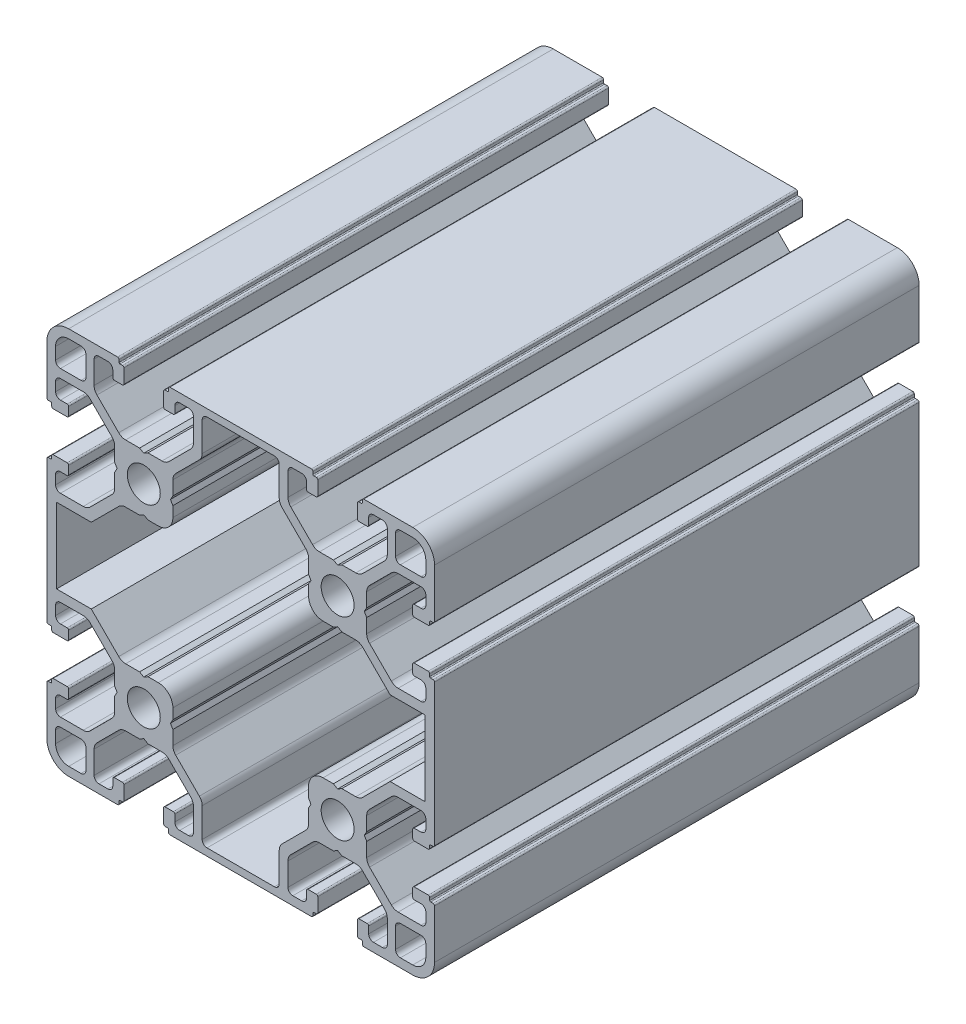
SolidWorks part; units mm, degrees
ref_plane "前视基准面" through (0, 0, 0) normal (0, 0, 1) x (1, 0, 0)
ref_plane "上视基准面" through (0, 0, 0) normal (0, 1, 0) x (1, 0, 0)
ref_plane "右视基准面" through (0, 0, 0) normal (1, 0, 0) x (0, 0, -1)
sketch "草图1" plane through (0, 0, 0) normal (0, 0, 1) x (1, 0, 0)
  line L0 (-19.9196, 14.4542) -> (-17.7856, 14.4542)
  line L1 (-20.7856, 14.9542) -> (-19.9196, 14.4542)
  line L2 (-14.7856, 17.4542) -> (-14.7856, 19.5882)
  line L3 (-21.6516, 14.4542) -> (-20.7856, 14.9542)
  line L4 (-14.7856, 19.5882) -> (-15.2856, 20.4542)
  line L5 (-24.543, 14.4542) -> (-21.6516, 14.4542)
  line L6 (-15.2856, 20.4542) -> (-14.7856, 21.3202)
  line L7 (-14.7856, 21.3202) -> (-14.7856, 24.2116)
  line L8 (-31.6214, 8.2042) -> (-25.9572, 13.8684)
  line L9 (-38.7856, 8.2042) -> (-31.6214, 8.2042)
  line L10 (-14.1998, 25.6258) -> (-9.3214, 30.5042)
  line L11 (-38.7856, -7.2958) -> (-38.7856, 8.2042)
  line L12 (-31.6214, -7.2958) -> (-38.7856, -7.2958)
  line L13 (-8.7356, 31.9184) -> (-8.7356, 37.9542)
  line L14 (-25.9572, -12.96) -> (-31.6214, -7.2958)
  line L15 (-7.7356, 38.9542) -> (6.1644, 38.9542)
  line L16 (-21.6516, -13.5458) -> (-24.543, -13.5458)
  line L17 (-20.7856, -14.0458) -> (-21.6516, -13.5458)
  line L18 (7.1644, 37.9542) -> (7.1644, 31.9184)
  line L19 (-19.9196, -13.5458) -> (-20.7856, -14.0458)
  line L20 (-17.7856, -13.5458) -> (-19.9196, -13.5458)
  line L21 (7.7502, 30.5042) -> (12.6286, 25.6258)
  line L22 (-14.7856, -18.6798) -> (-14.7856, -16.5458)
  line L23 (13.2144, 24.2116) -> (13.2144, 21.3202)
  line L24 (-15.2856, -19.5458) -> (-14.7856, -18.6798)
  line L25 (13.2144, 21.3202) -> (13.7144, 20.4542)
  line L26 (-14.7856, -20.4118) -> (-15.2856, -19.5458)
  line L27 (13.7144, 20.4542) -> (13.2144, 19.5882)
  line L28 (-14.7856, -23.3032) -> (-14.7856, -20.4118)
  line L29 (13.2144, 19.5882) -> (13.2144, 17.4542)
  line L30 (-9.3214, -29.5958) -> (-14.1998, -24.7174)
  line L31 (16.2144, 14.4542) -> (18.3484, 14.4542)
  line L32 (18.3484, 14.4542) -> (19.2144, 14.9542)
  line L33 (-8.7356, -37.0458) -> (-8.7356, -31.01)
  line L34 (19.2144, 14.9542) -> (20.0804, 14.4542)
  line L35 (20.0804, 14.4542) -> (22.9717, 14.4542)
  line L36 (6.1644, -38.0458) -> (-7.7356, -38.0458)
  line L37 (24.386, 13.8684) -> (30.0502, 8.2042)
  line L38 (7.1644, -31.01) -> (7.1644, -37.0458)
  line L39 (30.0502, 8.2042) -> (37.2144, 8.2042)
  line L40 (37.2144, 8.2042) -> (37.2144, -7.2958)
  line L41 (12.6286, -24.7174) -> (7.7502, -29.5958)
  line L42 (37.2144, -7.2958) -> (30.0502, -7.2958)
  line L43 (30.0502, -7.2958) -> (24.386, -12.96)
  line L44 (13.2144, -20.4118) -> (13.2144, -23.3032)
  line L45 (13.7144, -19.5458) -> (13.2144, -20.4118)
  line L46 (22.9717, -13.5458) -> (20.0804, -13.5458)
  line L47 (13.2144, -18.6798) -> (13.7144, -19.5458)
  line L48 (20.0804, -13.5458) -> (19.2144, -14.0458)
  line L49 (13.2144, -16.5458) -> (13.2144, -18.6798)
  line L50 (19.2144, -14.0458) -> (18.3484, -13.5458)
  line L51 (18.3484, -13.5458) -> (16.2144, -13.5458)
  line L52 (-40.7856, -14.1458) -> (-40.7856, 15.0542)
  line L53 (-39.9856, 15.3542) -> (-40.4856, 15.3542)
  line L54 (-39.9856, -14.4458) -> (-40.4856, -14.4458)
  line L55 (-39.7856, 16.0542) -> (-39.7856, 15.5542)
  line L56 (-39.7856, -15.1458) -> (-39.7856, -14.6458)
  line L57 (-36.5856, 16.3542) -> (-39.4856, 16.3542)
  line L58 (-36.5856, -15.4458) -> (-39.4856, -15.4458)
  line L59 (-36.2856, 14.3542) -> (-36.2856, 16.0542)
  line L60 (-36.2856, -13.4458) -> (-36.2856, -15.1458)
  line L61 (-37.9856, 14.0542) -> (-36.5856, 14.0542)
  line L62 (-37.9856, -13.1458) -> (-36.5856, -13.1458)
  line L63 (-38.9856, 11.2042) -> (-38.9856, 13.0542)
  line L64 (-38.9856, -10.2958) -> (-38.9856, -12.1458)
  line L65 (-33.2783, 10.2042) -> (-37.9856, 10.2042)
  line L66 (-33.2783, -9.2958) -> (-37.9856, -9.2958)
  line L67 (-27.3714, 15.2826) -> (-31.864, 10.79)
  line L68 (-27.3714, -14.3742) -> (-31.864, -9.8816)
  line L69 (-26.7856, 19.5882) -> (-26.7856, 16.6968)
  line L70 (-26.2856, 20.4542) -> (-26.7856, 19.5882)
  line L71 (-26.7856, -18.6798) -> (-26.7856, -15.7884)
  line L72 (-26.2856, 20.4542) -> (-26.7856, 21.3202)
  line L73 (-26.2856, -19.5458) -> (-26.7856, -18.6798)
  line L74 (-26.7856, 24.2116) -> (-26.7856, 21.3202)
  line L75 (-26.2856, -19.5458) -> (-26.7856, -20.4118)
  line L76 (-26.7856, -23.3032) -> (-26.7856, -20.4118)
  line L77 (-31.864, 30.1184) -> (-27.3714, 25.6258)
  line L78 (-31.864, -29.21) -> (-27.3714, -24.7174)
  line L79 (-37.9856, 30.7042) -> (-33.2783, 30.7042)
  line L80 (-37.9856, -29.7958) -> (-33.2783, -29.7958)
  line L81 (-38.9856, 27.8542) -> (-38.9856, 29.7042)
  line L82 (-38.9856, -26.9458) -> (-38.9856, -28.7958)
  line L83 (-36.5856, 26.8542) -> (-37.9856, 26.8542)
  line L84 (-36.5856, -25.9458) -> (-37.9856, -25.9458)
  line L85 (-36.2856, 24.8542) -> (-36.2856, 26.5542)
  line L86 (-36.2856, -23.9458) -> (-36.2856, -25.6458)
  line L87 (-39.4856, 24.5542) -> (-36.5856, 24.5542)
  line L88 (-39.4856, -23.6458) -> (-36.5856, -23.6458)
  line L89 (-39.7856, 25.3542) -> (-39.7856, 24.8542)
  line L90 (-39.7856, -24.4458) -> (-39.7856, -23.9458)
  line L91 (-40.4856, 25.5542) -> (-39.9856, 25.5542)
  line L92 (-40.4856, -24.6458) -> (-39.9856, -24.6458)
  line L93 (-40.7856, 35.9542) -> (-40.7856, 25.8542)
  line L94 (-40.7856, -35.0458) -> (-40.7856, -24.9458)
  line L95 (-26.1856, 40.4542) -> (-36.2856, 40.4542)
  line L96 (-26.1856, -39.5458) -> (-36.2856, -39.5458)
  line L97 (-25.8856, 39.6542) -> (-25.8856, 40.1542)
  line L98 (-25.8856, -38.7458) -> (-25.8856, -39.2458)
  line L99 (-25.1856, 39.4542) -> (-25.6856, 39.4542)
  line L100 (-25.1856, -38.5458) -> (-25.6856, -38.5458)
  line L101 (-24.8856, 36.2542) -> (-24.8856, 39.1542)
  line L102 (-24.8856, -35.3458) -> (-24.8856, -38.2458)
  line L103 (-26.8856, 35.9542) -> (-25.1856, 35.9542)
  line L104 (-26.8856, -35.0458) -> (-25.1856, -35.0458)
  line L105 (-27.1856, 37.6542) -> (-27.1856, 36.2542)
  line L106 (-27.1856, -36.7458) -> (-27.1856, -35.3458)
  line L107 (-30.0356, 38.6542) -> (-28.1856, 38.6542)
  line L108 (-30.0356, -37.7458) -> (-28.1856, -37.7458)
  line L109 (-31.0356, 32.9468) -> (-31.0356, 37.6542)
  line L110 (-31.0356, -32.0384) -> (-31.0356, -36.7458)
  line L111 (-25.9572, 27.04) -> (-30.4498, 31.5326)
  line L112 (-25.9572, -26.1316) -> (-30.4498, -30.6242)
  line L113 (-21.6516, 26.4542) -> (-24.543, 26.4542)
  line L114 (-20.7856, 25.9542) -> (-21.6516, 26.4542)
  line L115 (-21.6516, -25.5458) -> (-24.543, -25.5458)
  line L116 (-20.7856, 25.9542) -> (-19.9196, 26.4542)
  line L117 (-20.7856, -25.0458) -> (-21.6516, -25.5458)
  line L118 (-17.0283, 26.4542) -> (-19.9196, 26.4542)
  line L119 (-20.7856, -25.0458) -> (-19.9196, -25.5458)
  line L120 (-17.0283, -25.5458) -> (-19.9196, -25.5458)
  line L121 (-11.1214, 31.5326) -> (-15.614, 27.04)
  line L122 (-11.1214, -30.6242) -> (-15.614, -26.1316)
  line L123 (-10.5356, 37.6542) -> (-10.5356, 32.9468)
  line L124 (-10.5356, -36.7458) -> (-10.5356, -32.0384)
  line L125 (-13.3856, 38.6542) -> (-11.5356, 38.6542)
  line L126 (-13.3856, -37.7458) -> (-11.5356, -37.7458)
  line L127 (-14.3856, 36.2542) -> (-14.3856, 37.6542)
  line L128 (-14.3856, -35.3458) -> (-14.3856, -36.7458)
  line L129 (-16.3856, 35.9542) -> (-14.6856, 35.9542)
  line L130 (-16.3856, -35.0458) -> (-14.6856, -35.0458)
  line L131 (-16.6856, 39.1542) -> (-16.6856, 36.2542)
  line L132 (-16.6856, -38.2458) -> (-16.6856, -35.3458)
  line L133 (-15.8856, 39.4542) -> (-16.3856, 39.4542)
  line L134 (-15.8856, -38.5458) -> (-16.3856, -38.5458)
  line L135 (-15.6856, 40.1542) -> (-15.6856, 39.6542)
  line L136 (-15.6856, -39.2458) -> (-15.6856, -38.7458)
  line L137 (13.8144, 40.4542) -> (-15.3856, 40.4542)
  line L138 (13.8144, -39.5458) -> (-15.3856, -39.5458)
  line L139 (14.1144, 40.1542) -> (14.1144, 39.6542)
  line L140 (14.1144, -39.2458) -> (14.1144, -38.7458)
  line L141 (14.3144, 39.4542) -> (14.8144, 39.4542)
  line L142 (14.3144, -38.5458) -> (14.8144, -38.5458)
  line L143 (15.1144, 39.1542) -> (15.1144, 36.2542)
  line L144 (15.1144, -38.2458) -> (15.1144, -35.3458)
  line L145 (14.8144, 35.9542) -> (13.1144, 35.9542)
  line L146 (14.8144, -35.0458) -> (13.1144, -35.0458)
  line L147 (12.8144, 36.2542) -> (12.8144, 37.6542)
  line L148 (12.8144, -35.3458) -> (12.8144, -36.7458)
  line L149 (11.8144, 38.6542) -> (9.9644, 38.6542)
  line L150 (11.8144, -37.7458) -> (9.9644, -37.7458)
  line L151 (8.9644, 37.6542) -> (8.9644, 32.9468)
  line L152 (8.9644, -36.7458) -> (8.9644, -32.0384)
  line L153 (9.5502, 31.5326) -> (14.0428, 27.04)
  line L154 (9.5502, -30.6242) -> (14.0428, -26.1316)
  line L155 (15.457, 26.4542) -> (18.3484, 26.4542)
  line L156 (19.2144, 25.9542) -> (18.3484, 26.4542)
  line L157 (15.457, -25.5458) -> (18.3484, -25.5458)
  line L158 (19.2144, 25.9542) -> (20.0804, 26.4542)
  line L159 (19.2144, -25.0458) -> (18.3484, -25.5458)
  line L160 (20.0804, 26.4542) -> (22.9717, 26.4542)
  line L161 (19.2144, -25.0458) -> (20.0804, -25.5458)
  line L162 (20.0804, -25.5458) -> (22.9717, -25.5458)
  line L163 (24.386, 27.04) -> (28.8786, 31.5326)
  line L164 (24.386, -26.1316) -> (28.8786, -30.6242)
  line L165 (29.4644, 32.9468) -> (29.4644, 37.6542)
  line L166 (29.4644, -32.0384) -> (29.4644, -36.7458)
  line L167 (28.4644, 38.6542) -> (26.6144, 38.6542)
  line L168 (28.4644, -37.7458) -> (26.6144, -37.7458)
  line L169 (25.6144, 37.6542) -> (25.6144, 36.2542)
  line L170 (25.6144, -36.7458) -> (25.6144, -35.3458)
  line L171 (25.3144, 35.9542) -> (23.6144, 35.9542)
  line L172 (25.3144, -35.0458) -> (23.6144, -35.0458)
  line L173 (23.3144, 36.2542) -> (23.3144, 39.1542)
  line L174 (23.3144, -35.3458) -> (23.3144, -38.2458)
  line L175 (23.6144, 39.4542) -> (24.1144, 39.4542)
  line L176 (23.6144, -38.5458) -> (24.1144, -38.5458)
  line L177 (24.3144, 39.6542) -> (24.3144, 40.1542)
  line L178 (24.3144, -38.7458) -> (24.3144, -39.2458)
  line L179 (24.6144, 40.4542) -> (34.7144, 40.4542)
  line L180 (24.6144, -39.5458) -> (34.7144, -39.5458)
  line L181 (39.2144, 35.9542) -> (39.2144, 25.8542)
  line L182 (39.2144, -35.0458) -> (39.2144, -24.9458)
  line L183 (38.9144, 25.5542) -> (38.4144, 25.5542)
  line L184 (38.9144, -24.6458) -> (38.4144, -24.6458)
  line L185 (38.2144, 25.3542) -> (38.2144, 24.8542)
  line L186 (38.2144, -24.4458) -> (38.2144, -23.9458)
  line L187 (37.9144, 24.5542) -> (35.0144, 24.5542)
  line L188 (37.9144, -23.6458) -> (35.0144, -23.6458)
  line L189 (34.7144, 24.8542) -> (34.7144, 26.5542)
  line L190 (34.7144, -23.9458) -> (34.7144, -25.6458)
  line L191 (35.0144, 26.8542) -> (36.4144, 26.8542)
  line L192 (35.0144, -25.9458) -> (36.4144, -25.9458)
  line L193 (37.4144, 27.8542) -> (37.4144, 29.7042)
  line L194 (37.4144, -26.9458) -> (37.4144, -28.7958)
  line L195 (36.4144, 30.7042) -> (31.707, 30.7042)
  line L196 (36.4144, -29.7958) -> (31.707, -29.7958)
  line L197 (30.2928, 30.1184) -> (25.8002, 25.6258)
  line L198 (30.2928, -29.21) -> (25.8002, -24.7174)
  line L199 (25.2144, 24.2116) -> (25.2144, 21.3202)
  line L200 (24.7144, 20.4542) -> (25.2144, 21.3202)
  line L201 (25.2144, -23.3032) -> (25.2144, -20.4118)
  line L202 (24.7144, 20.4542) -> (25.2144, 19.5882)
  line L203 (24.7144, -19.5458) -> (25.2144, -20.4118)
  line L204 (25.2144, 19.5882) -> (25.2144, 16.6968)
  line L205 (24.7144, -19.5458) -> (25.2144, -18.6798)
  line L206 (25.2144, -18.6798) -> (25.2144, -15.7884)
  line L207 (25.8002, 15.2826) -> (30.2928, 10.79)
  line L208 (25.8002, -14.3742) -> (30.2928, -9.8816)
  line L209 (31.707, 10.2042) -> (36.4144, 10.2042)
  line L210 (31.707, -9.2958) -> (36.4144, -9.2958)
  line L211 (37.4144, 11.2042) -> (37.4144, 13.0542)
  line L212 (37.4144, -10.2958) -> (37.4144, -12.1458)
  line L213 (36.4144, 14.0542) -> (35.0144, 14.0542)
  line L214 (36.4144, -13.1458) -> (35.0144, -13.1458)
  line L215 (34.7144, 14.3542) -> (34.7144, 16.0542)
  line L216 (34.7144, -13.4458) -> (34.7144, -15.1458)
  line L217 (35.0144, 16.3542) -> (37.9144, 16.3542)
  line L218 (35.0144, -15.4458) -> (37.9144, -15.4458)
  line L219 (38.2144, 16.0542) -> (38.2144, 15.5542)
  line L220 (38.2144, -15.1458) -> (38.2144, -14.6458)
  line L221 (38.4144, 15.3542) -> (38.9144, 15.3542)
  line L222 (38.4144, -14.4458) -> (38.9144, -14.4458)
  line L223 (39.2144, -14.1458) -> (39.2144, 15.0542)
  line L224 (-33.7356, 38.6542) -> (-36.2856, 38.6542)
  line L225 (-38.9856, 33.5042) -> (-38.9856, 35.9542)
  line L226 (-32.7356, 33.5042) -> (-32.7356, 37.6542)
  line L227 (-37.9856, 32.5042) -> (-33.7356, 32.5042)
  line L228 (32.1644, 38.6542) -> (34.7144, 38.6542)
  line L229 (37.4144, 35.9542) -> (37.4144, 33.5042)
  line L230 (31.1644, 33.5042) -> (31.1644, 37.6542)
  line L231 (36.4144, 32.5042) -> (32.1644, 32.5042)
  line L232 (-38.9856, -35.0458) -> (-38.9856, -32.5958)
  line L233 (-37.9856, -31.5958) -> (-33.7356, -31.5958)
  line L234 (-33.7356, -37.7458) -> (-36.2856, -37.7458)
  line L235 (-32.7356, -32.5958) -> (-32.7356, -36.7458)
  line L236 (37.4144, -35.0458) -> (37.4144, -32.5958)
  line L237 (32.1644, -37.7458) -> (34.7144, -37.7458)
  line L238 (36.4144, -31.5958) -> (32.1644, -31.5958)
  line L239 (31.1644, -32.5958) -> (31.1644, -36.7458)
  circle A0 centre (19.2144, -19.5458) radius 3.4
  circle A1 centre (-20.7856, -19.5458) radius 3.4
  circle A2 centre (-20.7856, 20.4542) radius 3.4
  circle A3 centre (19.2144, 20.4542) radius 3.4
  arc A4 (-17.7856, 14.4542) -> (-14.7856, 17.4542) centre (-17.7856, 17.4542) ccw
  arc A5 (-24.543, 14.4542) -> (-25.9572, 13.8684) centre (-24.543, 12.4542) ccw
  arc A6 (-14.1998, 25.6258) -> (-14.7856, 24.2116) centre (-12.7856, 24.2116) ccw
  arc A7 (-9.3214, 30.5042) -> (-8.7356, 31.9184) centre (-10.7356, 31.9184) ccw
  arc A8 (-7.7356, 38.9542) -> (-8.7356, 37.9542) centre (-7.7356, 37.9542) ccw
  arc A9 (-25.9572, -12.96) -> (-24.543, -13.5458) centre (-24.543, -11.5458) ccw
  arc A10 (7.1644, 37.9542) -> (6.1644, 38.9542) centre (6.1644, 37.9542) ccw
  arc A11 (7.1644, 31.9184) -> (7.7502, 30.5042) centre (9.1644, 31.9184) ccw
  arc A12 (-14.7856, -16.5458) -> (-17.7856, -13.5458) centre (-17.7856, -16.5458) ccw
  arc A13 (13.2144, 24.2116) -> (12.6286, 25.6258) centre (11.2144, 24.2116) ccw
  arc A14 (-14.7856, -23.3032) -> (-14.1998, -24.7174) centre (-12.7856, -23.3032) ccw
  arc A15 (13.2144, 17.4542) -> (16.2144, 14.4542) centre (16.2144, 17.4542) ccw
  arc A16 (-8.7356, -31.01) -> (-9.3214, -29.5958) centre (-10.7356, -31.01) ccw
  arc A17 (-8.7356, -37.0458) -> (-7.7356, -38.0458) centre (-7.7356, -37.0458) ccw
  arc A18 (24.386, 13.8684) -> (22.9717, 14.4542) centre (22.9717, 12.4542) ccw
  arc A19 (6.1644, -38.0458) -> (7.1644, -37.0458) centre (6.1644, -37.0458) ccw
  arc A20 (7.7502, -29.5958) -> (7.1644, -31.01) centre (9.1644, -31.01) ccw
  arc A21 (12.6286, -24.7174) -> (13.2144, -23.3032) centre (11.2144, -23.3032) ccw
  arc A22 (22.9717, -13.5458) -> (24.386, -12.96) centre (22.9717, -11.5458) ccw
  arc A23 (16.2144, -13.5458) -> (13.2144, -16.5458) centre (16.2144, -16.5458) ccw
  arc A24 (-40.4856, 15.3542) -> (-40.7856, 15.0542) centre (-40.4856, 15.0542) ccw
  arc A25 (-40.7856, -14.1458) -> (-40.4856, -14.4458) centre (-40.4856, -14.1458) ccw
  arc A26 (-39.9856, 15.3542) -> (-39.7856, 15.5542) centre (-39.9856, 15.5542) ccw
  arc A27 (-39.7856, -14.6458) -> (-39.9856, -14.4458) centre (-39.9856, -14.6458) ccw
  arc A28 (-39.4856, 16.3542) -> (-39.7856, 16.0542) centre (-39.4856, 16.0542) ccw
  arc A29 (-39.7856, -15.1458) -> (-39.4856, -15.4458) centre (-39.4856, -15.1458) ccw
  arc A30 (-36.2856, 16.0542) -> (-36.5856, 16.3542) centre (-36.5856, 16.0542) ccw
  arc A31 (-36.5856, -15.4458) -> (-36.2856, -15.1458) centre (-36.5856, -15.1458) ccw
  arc A32 (-36.5856, 14.0542) -> (-36.2856, 14.3542) centre (-36.5856, 14.3542) ccw
  arc A33 (-36.2856, -13.4458) -> (-36.5856, -13.1458) centre (-36.5856, -13.4458) ccw
  arc A34 (-37.9856, 14.0542) -> (-38.9856, 13.0542) centre (-37.9856, 13.0542) ccw
  arc A35 (-38.9856, -12.1458) -> (-37.9856, -13.1458) centre (-37.9856, -12.1458) ccw
  arc A36 (-38.9856, 11.2042) -> (-37.9856, 10.2042) centre (-37.9856, 11.2042) ccw
  arc A37 (-37.9856, -9.2958) -> (-38.9856, -10.2958) centre (-37.9856, -10.2958) ccw
  arc A38 (-33.2783, 10.2042) -> (-31.864, 10.79) centre (-33.2783, 12.2042) ccw
  arc A39 (-31.864, -9.8816) -> (-33.2783, -9.2958) centre (-33.2783, -11.2958) ccw
  arc A40 (-27.3714, 15.2826) -> (-26.7856, 16.6968) centre (-28.7856, 16.6968) ccw
  arc A41 (-26.7856, -15.7884) -> (-27.3714, -14.3742) centre (-28.7856, -15.7884) ccw
  arc A42 (-26.7856, 24.2116) -> (-27.3714, 25.6258) centre (-28.7856, 24.2116) ccw
  arc A43 (-27.3714, -24.7174) -> (-26.7856, -23.3032) centre (-28.7856, -23.3032) ccw
  arc A44 (-31.864, 30.1184) -> (-33.2783, 30.7042) centre (-33.2783, 28.7042) ccw
  arc A45 (-33.2783, -29.7958) -> (-31.864, -29.21) centre (-33.2783, -27.7958) ccw
  arc A46 (-37.9856, 30.7042) -> (-38.9856, 29.7042) centre (-37.9856, 29.7042) ccw
  arc A47 (-38.9856, -28.7958) -> (-37.9856, -29.7958) centre (-37.9856, -28.7958) ccw
  arc A48 (-38.9856, 27.8542) -> (-37.9856, 26.8542) centre (-37.9856, 27.8542) ccw
  arc A49 (-37.9856, -25.9458) -> (-38.9856, -26.9458) centre (-37.9856, -26.9458) ccw
  arc A50 (-36.2856, 26.5542) -> (-36.5856, 26.8542) centre (-36.5856, 26.5542) ccw
  arc A51 (-36.5856, -25.9458) -> (-36.2856, -25.6458) centre (-36.5856, -25.6458) ccw
  arc A52 (-36.5856, 24.5542) -> (-36.2856, 24.8542) centre (-36.5856, 24.8542) ccw
  arc A53 (-36.2856, -23.9458) -> (-36.5856, -23.6458) centre (-36.5856, -23.9458) ccw
  arc A54 (-39.7856, 24.8542) -> (-39.4856, 24.5542) centre (-39.4856, 24.8542) ccw
  arc A55 (-39.4856, -23.6458) -> (-39.7856, -23.9458) centre (-39.4856, -23.9458) ccw
  arc A56 (-39.7856, 25.3542) -> (-39.9856, 25.5542) centre (-39.9856, 25.3542) ccw
  arc A57 (-39.9856, -24.6458) -> (-39.7856, -24.4458) centre (-39.9856, -24.4458) ccw
  arc A58 (-40.7856, 25.8542) -> (-40.4856, 25.5542) centre (-40.4856, 25.8542) ccw
  arc A59 (-40.4856, -24.6458) -> (-40.7856, -24.9458) centre (-40.4856, -24.9458) ccw
  arc A60 (-36.2856, 40.4542) -> (-40.7856, 35.9542) centre (-36.2856, 35.9542) ccw
  arc A61 (-40.7856, -35.0458) -> (-36.2856, -39.5458) centre (-36.2856, -35.0458) ccw
  arc A62 (-25.8856, 40.1542) -> (-26.1856, 40.4542) centre (-26.1856, 40.1542) ccw
  arc A63 (-26.1856, -39.5458) -> (-25.8856, -39.2458) centre (-26.1856, -39.2458) ccw
  arc A64 (-25.8856, 39.6542) -> (-25.6856, 39.4542) centre (-25.6856, 39.6542) ccw
  arc A65 (-25.6856, -38.5458) -> (-25.8856, -38.7458) centre (-25.6856, -38.7458) ccw
  arc A66 (-24.8856, 39.1542) -> (-25.1856, 39.4542) centre (-25.1856, 39.1542) ccw
  arc A67 (-25.1856, -38.5458) -> (-24.8856, -38.2458) centre (-25.1856, -38.2458) ccw
  arc A68 (-25.1856, 35.9542) -> (-24.8856, 36.2542) centre (-25.1856, 36.2542) ccw
  arc A69 (-24.8856, -35.3458) -> (-25.1856, -35.0458) centre (-25.1856, -35.3458) ccw
  arc A70 (-27.1856, 36.2542) -> (-26.8856, 35.9542) centre (-26.8856, 36.2542) ccw
  arc A71 (-26.8856, -35.0458) -> (-27.1856, -35.3458) centre (-26.8856, -35.3458) ccw
  arc A72 (-27.1856, 37.6542) -> (-28.1856, 38.6542) centre (-28.1856, 37.6542) ccw
  arc A73 (-28.1856, -37.7458) -> (-27.1856, -36.7458) centre (-28.1856, -36.7458) ccw
  arc A74 (-30.0356, 38.6542) -> (-31.0356, 37.6542) centre (-30.0356, 37.6542) ccw
  arc A75 (-31.0356, -36.7458) -> (-30.0356, -37.7458) centre (-30.0356, -36.7458) ccw
  arc A76 (-31.0356, 32.9468) -> (-30.4498, 31.5326) centre (-29.0356, 32.9468) ccw
  arc A77 (-30.4498, -30.6242) -> (-31.0356, -32.0384) centre (-29.0356, -32.0384) ccw
  arc A78 (-25.9572, 27.04) -> (-24.543, 26.4542) centre (-24.543, 28.4542) ccw
  arc A79 (-24.543, -25.5458) -> (-25.9572, -26.1316) centre (-24.543, -27.5458) ccw
  arc A80 (-17.0283, 26.4542) -> (-15.614, 27.04) centre (-17.0283, 28.4542) ccw
  arc A81 (-15.614, -26.1316) -> (-17.0283, -25.5458) centre (-17.0283, -27.5458) ccw
  arc A82 (-11.1214, 31.5326) -> (-10.5356, 32.9468) centre (-12.5356, 32.9468) ccw
  arc A83 (-10.5356, -32.0384) -> (-11.1214, -30.6242) centre (-12.5356, -32.0384) ccw
  arc A84 (-10.5356, 37.6542) -> (-11.5356, 38.6542) centre (-11.5356, 37.6542) ccw
  arc A85 (-11.5356, -37.7458) -> (-10.5356, -36.7458) centre (-11.5356, -36.7458) ccw
  arc A86 (-13.3856, 38.6542) -> (-14.3856, 37.6542) centre (-13.3856, 37.6542) ccw
  arc A87 (-14.3856, -36.7458) -> (-13.3856, -37.7458) centre (-13.3856, -36.7458) ccw
  arc A88 (-14.6856, 35.9542) -> (-14.3856, 36.2542) centre (-14.6856, 36.2542) ccw
  arc A89 (-14.3856, -35.3458) -> (-14.6856, -35.0458) centre (-14.6856, -35.3458) ccw
  arc A90 (-16.6856, 36.2542) -> (-16.3856, 35.9542) centre (-16.3856, 36.2542) ccw
  arc A91 (-16.3856, -35.0458) -> (-16.6856, -35.3458) centre (-16.3856, -35.3458) ccw
  arc A92 (-16.3856, 39.4542) -> (-16.6856, 39.1542) centre (-16.3856, 39.1542) ccw
  arc A93 (-16.6856, -38.2458) -> (-16.3856, -38.5458) centre (-16.3856, -38.2458) ccw
  arc A94 (-15.8856, 39.4542) -> (-15.6856, 39.6542) centre (-15.8856, 39.6542) ccw
  arc A95 (-15.6856, -38.7458) -> (-15.8856, -38.5458) centre (-15.8856, -38.7458) ccw
  arc A96 (-15.3856, 40.4542) -> (-15.6856, 40.1542) centre (-15.3856, 40.1542) ccw
  arc A97 (-15.6856, -39.2458) -> (-15.3856, -39.5458) centre (-15.3856, -39.2458) ccw
  arc A98 (14.1144, 40.1542) -> (13.8144, 40.4542) centre (13.8144, 40.1542) ccw
  arc A99 (13.8144, -39.5458) -> (14.1144, -39.2458) centre (13.8144, -39.2458) ccw
  arc A100 (14.1144, 39.6542) -> (14.3144, 39.4542) centre (14.3144, 39.6542) ccw
  arc A101 (14.3144, -38.5458) -> (14.1144, -38.7458) centre (14.3144, -38.7458) ccw
  arc A102 (15.1144, 39.1542) -> (14.8144, 39.4542) centre (14.8144, 39.1542) ccw
  arc A103 (14.8144, -38.5458) -> (15.1144, -38.2458) centre (14.8144, -38.2458) ccw
  arc A104 (14.8144, 35.9542) -> (15.1144, 36.2542) centre (14.8144, 36.2542) ccw
  arc A105 (15.1144, -35.3458) -> (14.8144, -35.0458) centre (14.8144, -35.3458) ccw
  arc A106 (12.8144, 36.2542) -> (13.1144, 35.9542) centre (13.1144, 36.2542) ccw
  arc A107 (13.1144, -35.0458) -> (12.8144, -35.3458) centre (13.1144, -35.3458) ccw
  arc A108 (12.8144, 37.6542) -> (11.8144, 38.6542) centre (11.8144, 37.6542) ccw
  arc A109 (11.8144, -37.7458) -> (12.8144, -36.7458) centre (11.8144, -36.7458) ccw
  arc A110 (9.9644, 38.6542) -> (8.9644, 37.6542) centre (9.9644, 37.6542) ccw
  arc A111 (8.9644, -36.7458) -> (9.9644, -37.7458) centre (9.9644, -36.7458) ccw
  arc A112 (8.9644, 32.9468) -> (9.5502, 31.5326) centre (10.9644, 32.9468) ccw
  arc A113 (9.5502, -30.6242) -> (8.9644, -32.0384) centre (10.9644, -32.0384) ccw
  arc A114 (14.0428, 27.04) -> (15.457, 26.4542) centre (15.457, 28.4542) ccw
  arc A115 (15.457, -25.5458) -> (14.0428, -26.1316) centre (15.457, -27.5458) ccw
  arc A116 (22.9717, 26.4542) -> (24.386, 27.04) centre (22.9717, 28.4542) ccw
  arc A117 (24.386, -26.1316) -> (22.9717, -25.5458) centre (22.9717, -27.5458) ccw
  arc A118 (28.8786, 31.5326) -> (29.4644, 32.9468) centre (27.4644, 32.9468) ccw
  arc A119 (29.4644, -32.0384) -> (28.8786, -30.6242) centre (27.4644, -32.0384) ccw
  arc A120 (29.4644, 37.6542) -> (28.4644, 38.6542) centre (28.4644, 37.6542) ccw
  arc A121 (28.4644, -37.7458) -> (29.4644, -36.7458) centre (28.4644, -36.7458) ccw
  arc A122 (26.6144, 38.6542) -> (25.6144, 37.6542) centre (26.6144, 37.6542) ccw
  arc A123 (25.6144, -36.7458) -> (26.6144, -37.7458) centre (26.6144, -36.7458) ccw
  arc A124 (25.3144, 35.9542) -> (25.6144, 36.2542) centre (25.3144, 36.2542) ccw
  arc A125 (25.6144, -35.3458) -> (25.3144, -35.0458) centre (25.3144, -35.3458) ccw
  arc A126 (23.3144, 36.2542) -> (23.6144, 35.9542) centre (23.6144, 36.2542) ccw
  arc A127 (23.6144, -35.0458) -> (23.3144, -35.3458) centre (23.6144, -35.3458) ccw
  arc A128 (23.6144, 39.4542) -> (23.3144, 39.1542) centre (23.6144, 39.1542) ccw
  arc A129 (23.3144, -38.2458) -> (23.6144, -38.5458) centre (23.6144, -38.2458) ccw
  arc A130 (24.1144, 39.4542) -> (24.3144, 39.6542) centre (24.1144, 39.6542) ccw
  arc A131 (24.3144, -38.7458) -> (24.1144, -38.5458) centre (24.1144, -38.7458) ccw
  arc A132 (24.6144, 40.4542) -> (24.3144, 40.1542) centre (24.6144, 40.1542) ccw
  arc A133 (24.3144, -39.2458) -> (24.6144, -39.5458) centre (24.6144, -39.2458) ccw
  arc A134 (39.2144, 35.9542) -> (34.7144, 40.4542) centre (34.7144, 35.9542) ccw
  arc A135 (34.7144, -39.5458) -> (39.2144, -35.0458) centre (34.7144, -35.0458) ccw
  arc A136 (38.9144, 25.5542) -> (39.2144, 25.8542) centre (38.9144, 25.8542) ccw
  arc A137 (39.2144, -24.9458) -> (38.9144, -24.6458) centre (38.9144, -24.9458) ccw
  arc A138 (38.4144, 25.5542) -> (38.2144, 25.3542) centre (38.4144, 25.3542) ccw
  arc A139 (38.2144, -24.4458) -> (38.4144, -24.6458) centre (38.4144, -24.4458) ccw
  arc A140 (37.9144, 24.5542) -> (38.2144, 24.8542) centre (37.9144, 24.8542) ccw
  arc A141 (38.2144, -23.9458) -> (37.9144, -23.6458) centre (37.9144, -23.9458) ccw
  arc A142 (34.7144, 24.8542) -> (35.0144, 24.5542) centre (35.0144, 24.8542) ccw
  arc A143 (35.0144, -23.6458) -> (34.7144, -23.9458) centre (35.0144, -23.9458) ccw
  arc A144 (35.0144, 26.8542) -> (34.7144, 26.5542) centre (35.0144, 26.5542) ccw
  arc A145 (34.7144, -25.6458) -> (35.0144, -25.9458) centre (35.0144, -25.6458) ccw
  arc A146 (36.4144, 26.8542) -> (37.4144, 27.8542) centre (36.4144, 27.8542) ccw
  arc A147 (37.4144, -26.9458) -> (36.4144, -25.9458) centre (36.4144, -26.9458) ccw
  arc A148 (37.4144, 29.7042) -> (36.4144, 30.7042) centre (36.4144, 29.7042) ccw
  arc A149 (36.4144, -29.7958) -> (37.4144, -28.7958) centre (36.4144, -28.7958) ccw
  arc A150 (31.707, 30.7042) -> (30.2928, 30.1184) centre (31.707, 28.7042) ccw
  arc A151 (30.2928, -29.21) -> (31.707, -29.7958) centre (31.707, -27.7958) ccw
  arc A152 (25.8002, 25.6258) -> (25.2144, 24.2116) centre (27.2144, 24.2116) ccw
  arc A153 (25.2144, -23.3032) -> (25.8002, -24.7174) centre (27.2144, -23.3032) ccw
  arc A154 (25.2144, 16.6968) -> (25.8002, 15.2826) centre (27.2144, 16.6968) ccw
  arc A155 (25.8002, -14.3742) -> (25.2144, -15.7884) centre (27.2144, -15.7884) ccw
  arc A156 (30.2928, 10.79) -> (31.707, 10.2042) centre (31.707, 12.2042) ccw
  arc A157 (31.707, -9.2958) -> (30.2928, -9.8816) centre (31.707, -11.2958) ccw
  arc A158 (36.4144, 10.2042) -> (37.4144, 11.2042) centre (36.4144, 11.2042) ccw
  arc A159 (37.4144, -10.2958) -> (36.4144, -9.2958) centre (36.4144, -10.2958) ccw
  arc A160 (37.4144, 13.0542) -> (36.4144, 14.0542) centre (36.4144, 13.0542) ccw
  arc A161 (36.4144, -13.1458) -> (37.4144, -12.1458) centre (36.4144, -12.1458) ccw
  arc A162 (34.7144, 14.3542) -> (35.0144, 14.0542) centre (35.0144, 14.3542) ccw
  arc A163 (35.0144, -13.1458) -> (34.7144, -13.4458) centre (35.0144, -13.4458) ccw
  arc A164 (35.0144, 16.3542) -> (34.7144, 16.0542) centre (35.0144, 16.0542) ccw
  arc A165 (34.7144, -15.1458) -> (35.0144, -15.4458) centre (35.0144, -15.1458) ccw
  arc A166 (38.2144, 16.0542) -> (37.9144, 16.3542) centre (37.9144, 16.0542) ccw
  arc A167 (37.9144, -15.4458) -> (38.2144, -15.1458) centre (37.9144, -15.1458) ccw
  arc A168 (38.2144, 15.5542) -> (38.4144, 15.3542) centre (38.4144, 15.5542) ccw
  arc A169 (38.4144, -14.4458) -> (38.2144, -14.6458) centre (38.4144, -14.6458) ccw
  arc A170 (39.2144, 15.0542) -> (38.9144, 15.3542) centre (38.9144, 15.0542) ccw
  arc A171 (38.9144, -14.4458) -> (39.2144, -14.1458) centre (38.9144, -14.1458) ccw
  arc A172 (-36.2856, 38.6542) -> (-38.9856, 35.9542) centre (-36.2856, 35.9542) ccw
  arc A173 (-32.7356, 37.6542) -> (-33.7356, 38.6542) centre (-33.7356, 37.6542) ccw
  arc A174 (-38.9856, 33.5042) -> (-37.9856, 32.5042) centre (-37.9856, 33.5042) ccw
  arc A175 (-33.7356, 32.5042) -> (-32.7356, 33.5042) centre (-33.7356, 33.5042) ccw
  arc A176 (37.4144, 35.9542) -> (34.7144, 38.6542) centre (34.7144, 35.9542) ccw
  arc A177 (32.1644, 38.6542) -> (31.1644, 37.6542) centre (32.1644, 37.6542) ccw
  arc A178 (36.4144, 32.5042) -> (37.4144, 33.5042) centre (36.4144, 33.5042) ccw
  arc A179 (31.1644, 33.5042) -> (32.1644, 32.5042) centre (32.1644, 33.5042) ccw
  arc A180 (-37.9856, -31.5958) -> (-38.9856, -32.5958) centre (-37.9856, -32.5958) ccw
  arc A181 (-38.9856, -35.0458) -> (-36.2856, -37.7458) centre (-36.2856, -35.0458) ccw
  arc A182 (-32.7356, -32.5958) -> (-33.7356, -31.5958) centre (-33.7356, -32.5958) ccw
  arc A183 (-33.7356, -37.7458) -> (-32.7356, -36.7458) centre (-33.7356, -36.7458) ccw
  arc A184 (34.7144, -37.7458) -> (37.4144, -35.0458) centre (34.7144, -35.0458) ccw
  arc A185 (37.4144, -32.5958) -> (36.4144, -31.5958) centre (36.4144, -32.5958) ccw
  arc A186 (31.1644, -36.7458) -> (32.1644, -37.7458) centre (32.1644, -36.7458) ccw
  arc A187 (32.1644, -31.5958) -> (31.1644, -32.5958) centre (32.1644, -32.5958) ccw
extrude "凸台-拉伸1" add sketch "草图1" along normal blind 100
